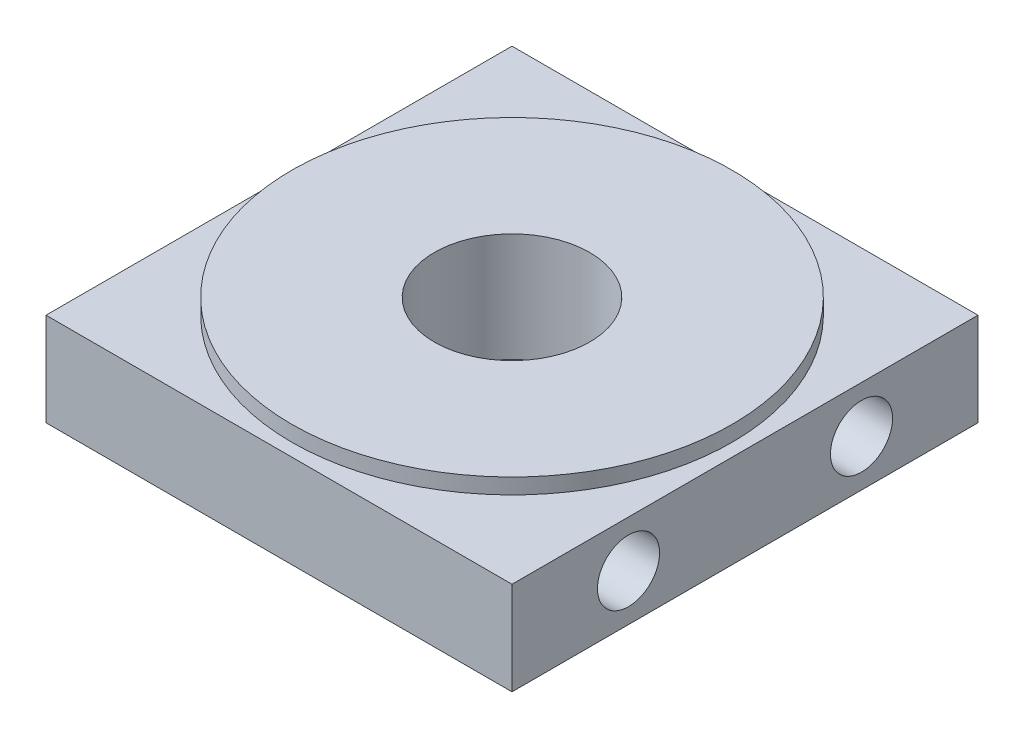
SolidWorks part; units mm, degrees
ref_plane "Front Plane" through (0, 0, 0) normal (0, 0, 1) x (1, 0, 0)
ref_plane "Top Plane" through (0, 0, 0) normal (0, 1, 0) x (1, 0, 0)
ref_plane "Right Plane" through (0, 0, 0) normal (1, 0, 0) x (0, 0, -1)
sketch "Sketch1" plane through (0, 0, 0) normal (0, 1, 0) x (1, 0, 0)
  line L1 (-19.976, 21.5635) -> (18.124, 21.5635)
  line L2 (-19.976, 21.5635) -> (-19.976, -16.5365)
  line L3 (-19.976, -16.5365) -> (18.124, -16.5365)
  line L4 (18.124, 21.5635) -> (18.124, -16.5365)
  line L5 (-19.976, 21.5635) -> (18.124, -16.5365) construction
  line L6 (-19.976, -16.5365) -> (18.124, 21.5635) construction
  point P0 (-0.926, 2.5135)
  dimension "D1" = 38.1
  dimension "D2" = 38.1
extrude "Boss-Extrude1" add sketch "Sketch1" along normal blind 7.62
sketch "Sketch2" plane through (0, 7.62, 0) normal (0, 1, 0) x (1, 0, 0)
  line L1 (-19.976, -16.5365) -> (18.124, -16.5365) construction
  line L2 (-19.976, 21.5635) -> (-19.976, -16.5365) construction
  circle A0 centre (-0.926, 2.5135) radius 18
  circle A1 centre (-0.926, 2.5135) radius 6.35
  dimension "D1" = 36
  dimension "D4" = 12.7
  dimension "D2" = 19.05
  dimension "D3" = 19.05
extrude "Boss-Extrude2" add sketch "Sketch2" along normal blind 1.27
sketch "Sketch4" plane through (-19.976, 0, 0) normal (-1, 0, 0) x (0, 0, 1)
  line L0 (-21.5635, 7.62) -> (-21.5635, 0) construction
  line L1 (16.5365, 7.62) -> (16.5365, 0) construction
  circle A0 centre (-12.0385, 3.81) radius 2.54
  circle A1 centre (7.0115, 3.81) radius 2.54
  point P14 (-21.5635, 3.81)
  dimension "D1" = 5.08
  dimension "D2" = 9.525
  dimension "D3" = 9.525
sketch "Sketch5" plane through (0, 7.62, 0) normal (0, 1, 0) x (1, 0, 0)
  circle A0 centre (-0.926, 2.5135) radius 6.35
extrude "Cut-Extrude1" cut sketch "Sketch5" against normal through all
extrude "Cut-Extrude2" cut sketch "Sketch4" against normal blind 7.62
sketch "Sketch6" plane through (18.124, 0, 0) normal (1, 0, 0) x (0, 0, -1)
  line L0 (-16.5365, 7.62) -> (-16.5365, 0) construction
  line L1 (21.5635, 7.62) -> (21.5635, 0) construction
  circle A0 centre (-7.0115, 3.81) radius 2.54
  circle A1 centre (12.0385, 3.81) radius 2.54
  point P6 (-16.5365, 3.81)
  point P9 (21.5635, 3.81)
  dimension "D1" = 5.08
  dimension "D2" = 9.525
  dimension "D3" = 9.525
extrude "Cut-Extrude3" cut sketch "Sketch6" against normal blind 7.62
